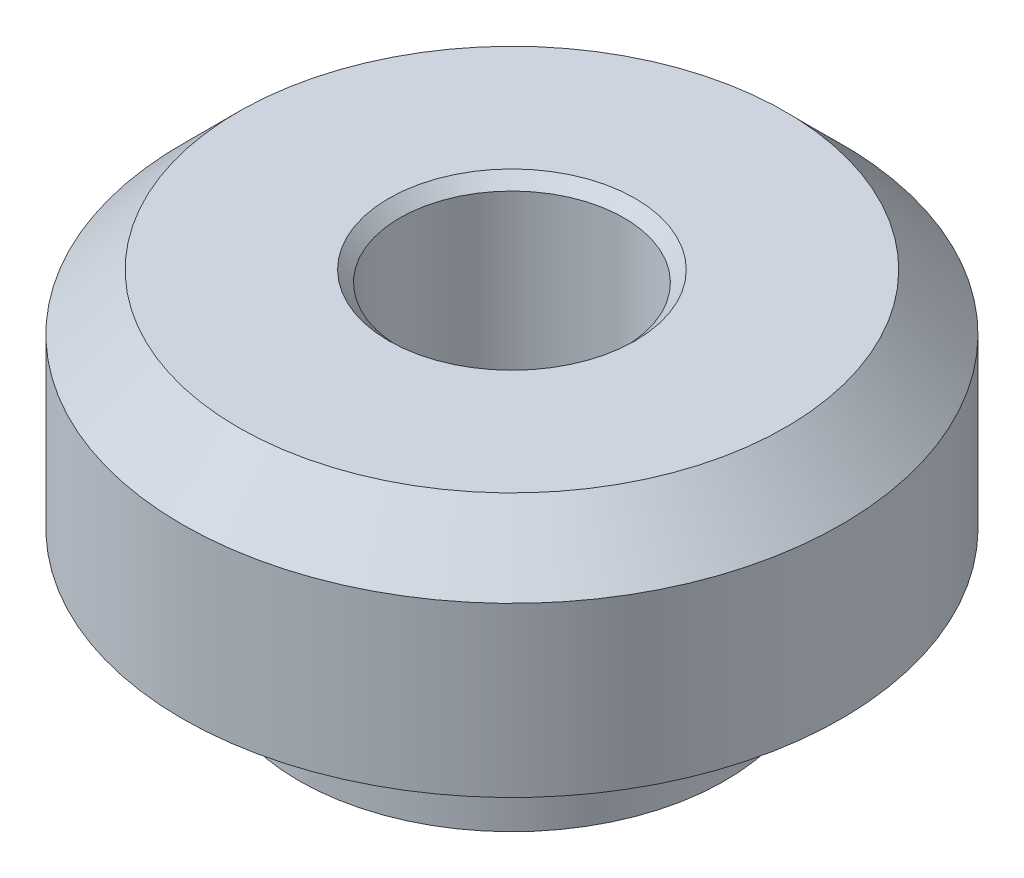
SolidWorks part; units mm, degrees
material "1023 Carbon Steel Sheet (SS)"
ref_plane "Front Plane" through (0, 0, 0) normal (0, 0, 1) x (1, 0, 0)
ref_plane "Top Plane" through (0, 0, 0) normal (0, 1, 0) x (1, 0, 0)
ref_plane "Right Plane" through (0, 0, 0) normal (1, 0, 0) x (0, 0, -1)
sketch "Sketch1" plane through (0, 0, 0) normal (0, 1, 0) x (1, 0, 0)
  circle A0 centre (0, 0) radius 1.9
extrude "Boss-Extrude1" add sketch "Sketch1" along normal blind 1
sketch "Sketch2" plane through (0, 1, 0) normal (0, 1, 0) x (1, 0, 0)
  circle A0 centre (0, 0) radius 2.9404
  dimension "D1" = 5.8808
extrude "Boss-Extrude2" add sketch "Sketch2" along normal blind 2
chamfer "Chamfer1" distance 0.5 angle 45 1 edges at (0, 3, 2.9404)
sketch "Sketch3" plane through (0, 3, 0) normal (0, 1, 0) x (1, 0, 0)
  circle A0 centre (0, 0) radius 1
  dimension "D1" = 2
extrude "Cut-Extrude1" cut sketch "Sketch3" against normal blind 4
chamfer "Chamfer2" distance 0.1 angle 45 1 edges at (0, 3, 1)
